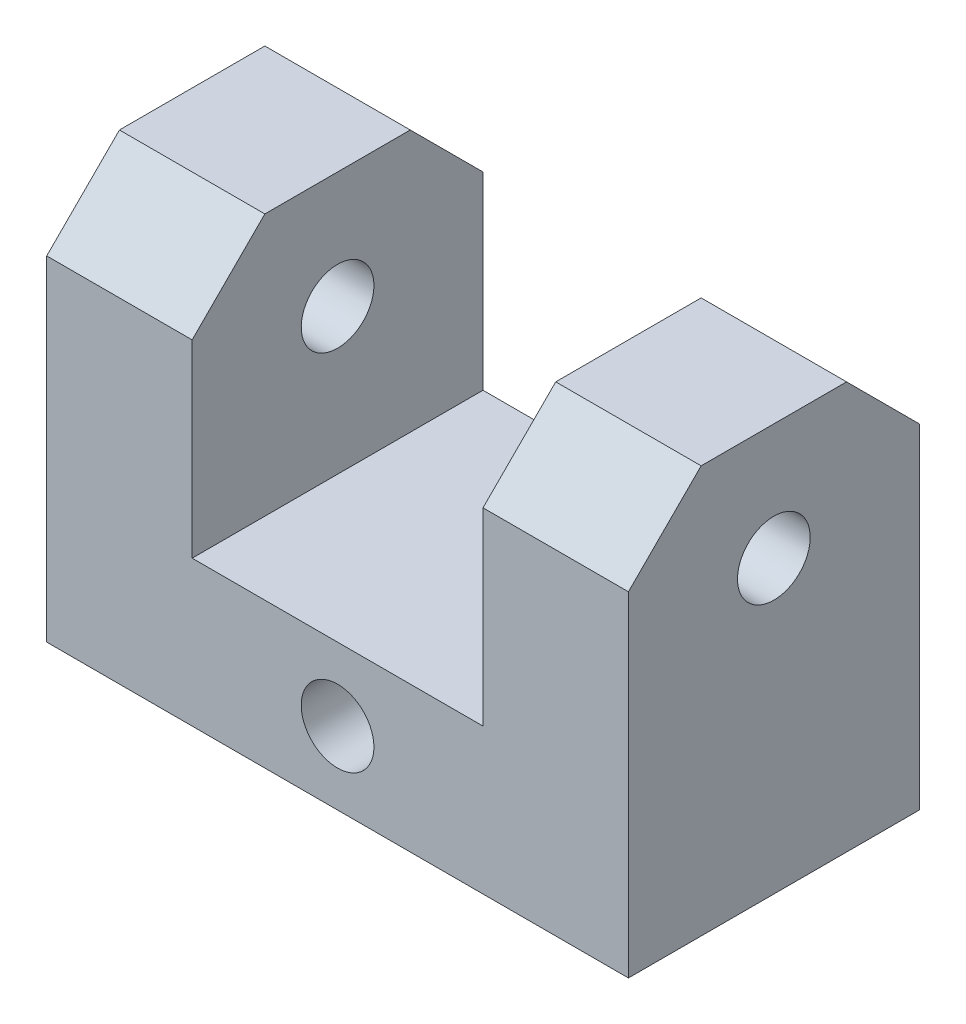
SolidWorks part; units mm, degrees
ref_plane "Front Plane" through (0, 0, 0) normal (0, 0, 1) x (1, 0, 0)
ref_plane "Top Plane" through (0, 0, 0) normal (0, 1, 0) x (1, 0, 0)
ref_plane "Right Plane" through (0, 0, 0) normal (1, 0, 0) x (0, 0, -1)
sketch "Sketch1" plane through (0, 0, 0) normal (0, 1, 0) x (1, 0, 0)
  line L1 (25.4, 12.7) -> (-25.4, 12.7)
  line L2 (25.4, 12.7) -> (25.4, -12.7)
  line L3 (25.4, -12.7) -> (-25.4, -12.7)
  line L4 (-25.4, 12.7) -> (-25.4, -12.7)
  line L5 (25.4, 12.7) -> (-25.4, -12.7) construction
  line L6 (25.4, -12.7) -> (-25.4, 12.7) construction
  point P0 (0, 0)
  dimension "D1" = 50.8
  dimension "D2" = 25.4
extrude "Boss-Extrude1" add sketch "Sketch1" along normal blind 35.56
sketch "Sketch2" plane through (0, 0, 12.7) normal (0, 0, 1) x (1, 0, 0)
  line L0 (-25.4, 35.56) -> (25.4, 35.56) construction
  line L1 (-12.7, 35.56) -> (12.7, 35.56)
  line L2 (-12.7, 35.56) -> (-12.7, 12.7)
  line L3 (-12.7, 12.7) -> (12.7, 12.7)
  line L4 (12.7, 35.56) -> (12.7, 12.7)
  line L5 (-25.4, 35.56) -> (-25.4, 0) construction
  line L6 (25.4, 35.56) -> (25.4, 0) construction
  line L7 (-25.4, 0) -> (25.4, 0) construction
  circle A0 centre (0, 6.35) radius 3.175
  point P6 (-12.7, 24.13)
  dimension "D4" = 6.35
  dimension "D5" = 6.35
  dimension "D1" = 12.7
  dimension "D2" = 12.7
  dimension "D3" = 12.7
  dimension "D6" = 25.4
extrude "Cut-Extrude1" cut sketch "Sketch2" against normal through all both and the other way through all
sketch "Sketch3" plane through (25.4, 0, 0) normal (1, 0, 0) x (0, 0, -1)
  line L0 (-12.7, 0) -> (12.7, 0) construction
  line L1 (12.7, 35.56) -> (12.7, 0) construction
  circle A0 centre (0, 25.4) radius 3.175
  dimension "D3" = 6.35
  dimension "D1" = 25.4
  dimension "D2" = 12.7
extrude "Cut-Extrude2" cut sketch "Sketch3" against normal through all both and the other way through all
chamfer "Chamfer2" distance 6.35 angle 45 4 edges at (-19.05, 35.56, 12.7) (-19.05, 35.56, -12.7) (19.05, 35.56, -12.7) (19.05, 35.56, 12.7)
